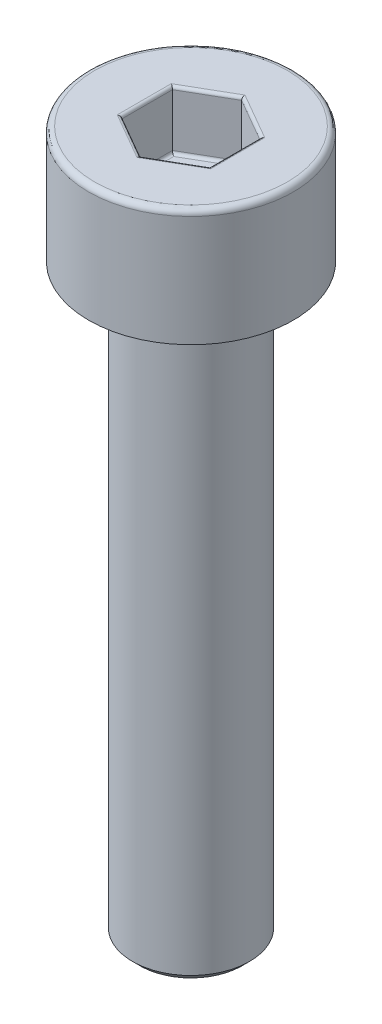
SolidWorks part; units mm, degrees
ref_plane "Front Plane" through (0, 0, 0) normal (0, 0, 1) x (1, 0, 0)
ref_plane "Top Plane" through (0, 0, 0) normal (0, 1, 0) x (1, 0, 0)
ref_plane "Right Plane" through (0, 0, 0) normal (1, 0, 0) x (0, 0, -1)
sketch "Sketch1" plane through (0, 0, 0) normal (0, 0, 1) x (1, 0, 0)
  line L0 (0, 0) -> (0, -47.0967) construction
  line L1 (0, -24) -> (-2, -24)
  line L2 (-2, -24) -> (-2, -4)
  line L3 (-2, -4) -> (-3.5, -4)
  line L4 (-3.5, -4) -> (-3.5, 0)
  line L5 (-3.5, 0) -> (0, 0)
  line L6 (0, 0) -> (0, -24)
  dimension "d" = 4
  dimension "l" = 24
  dimension "k" = 4
  dimension "dk" = 7
revolve "Revolve1" add sketch "Sketch1" angle 360 about L0
chamfer "Chamfer1" distance 0.25 angle 45 2 edges at (0, -4, 2) (0, -24, 2)
fillet "Fillet1" radius 0.2 1 edges at (0, 0, 3.5)
sketch "Sketch2" plane through (0, 0, 0) normal (0, 1, 0) x (1, 0, 0)
  line L1 (0, 1.7321) -> (-1.5, 0.866)
  line L2 (-1.5, 0.866) -> (-1.5, -0.866)
  line L3 (-1.5, -0.866) -> (0, -1.7321)
  line L4 (0, -1.7321) -> (1.5, -0.866)
  line L5 (1.5, -0.866) -> (1.5, 0.866)
  line L6 (1.5, 0.866) -> (0, 1.7321)
  circle A0 centre (0, 0) radius 1.5 construction
  dimension "s" = 3
extrude "Cut-Extrude1" cut sketch "Sketch2" against normal blind 2
fillet "Fillet2" radius 0.1 12 edges at (-0.75, 0, -1.299) (-1.5, 0, 0) (-0.75, 0, 1.299) (0.75, 0, 1.299) (1.5, 0, 0) (0.75, 0, -1.299) (1.5, -2, 0) (0.75, -2, 1.299) (-0.75, -2, 1.299) (-1.5, -2, 0) (-0.75, -2, -1.299) (0.75, -2, -1.299)
